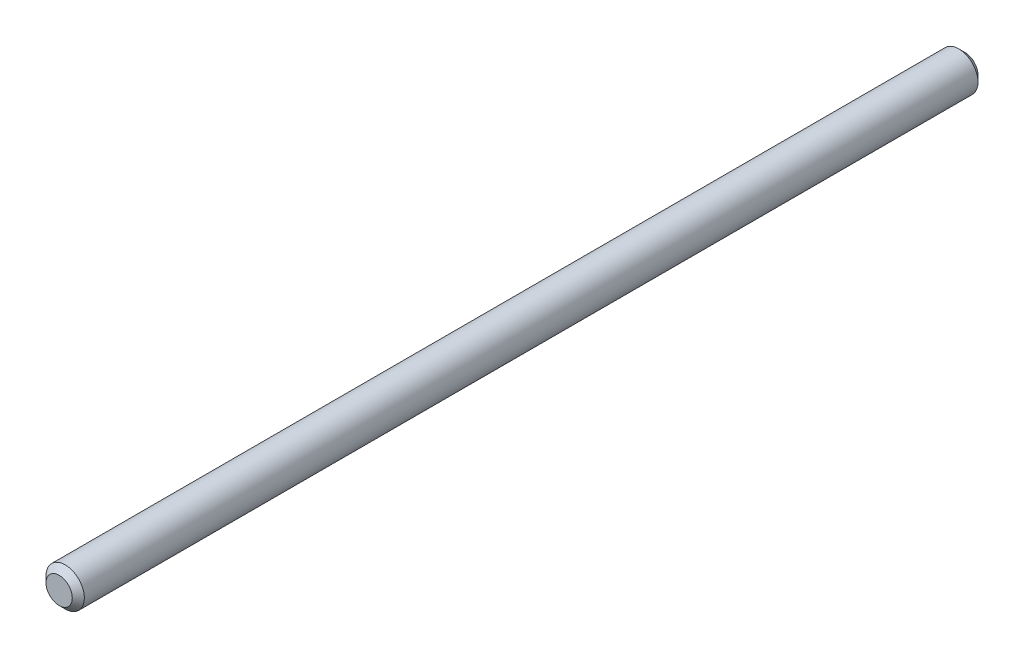
SolidWorks part; units mm, degrees
material "Brass"
ref_plane "Front Plane" through (0, 0, 0) normal (0, 0, 1) x (1, 0, 0)
ref_plane "Top Plane" through (0, 0, 0) normal (0, 1, 0) x (1, 0, 0)
ref_plane "Right Plane" through (0, 0, 0) normal (1, 0, 0) x (0, 0, -1)
sketch "Sketch1" plane through (0, 0, 0) normal (0, 0, 1) x (1, 0, 0)
  circle A0 centre (0, 0) radius 3.175
  dimension "D1" = 6.35
extrude "Boss-Extrude1" add sketch "Sketch1" along normal mid plane 150
chamfer "Chamfer1" distance 1 angle 45 2 edges at (3.175, 0, -75) (3.175, 0, 75)
